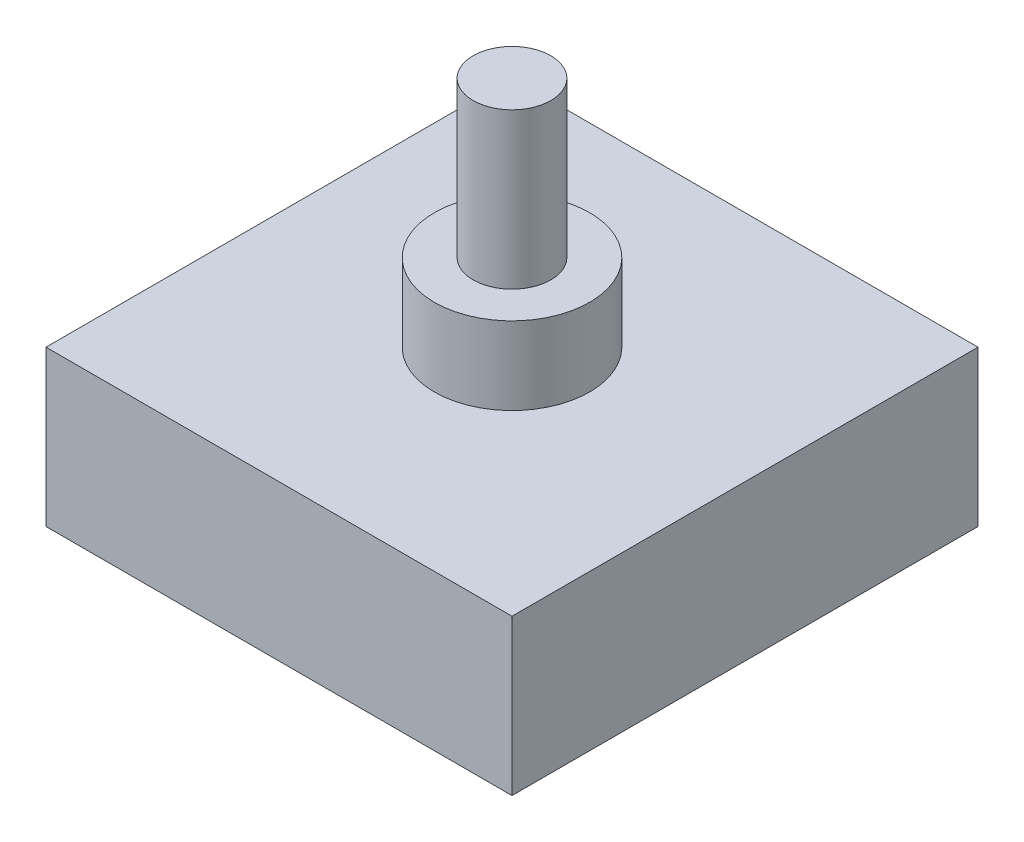
SolidWorks part; units mm, degrees
ref_plane "Front Plane" through (0, 0, 0) normal (0, 0, 1) x (1, 0, 0)
ref_plane "Top Plane" through (0, 0, 0) normal (0, 1, 0) x (1, 0, 0)
ref_plane "Right Plane" through (0, 0, 0) normal (1, 0, 0) x (0, 0, -1)
sketch "Sketch1" plane through (0, 0, 0) normal (0, 1, 0) x (1, 0, 0)
  line L0 (0, 139.7) -> (-74.1744, 139.7) construction
  line L5 (0, 177.8) -> (76.2, 177.8)
  line L6 (0, 177.8) -> (0, 101.6)
  line L7 (0, 101.6) -> (76.2, 101.6)
  line L8 (76.2, 177.8) -> (76.2, 101.6)
  line L9 (0, 279.4) -> (0, 0) construction
  dimension "D1" = 76.2
  dimension "D2" = 76.2
  dimension "D3" = 139.7
extrude "Boss-Extrude1" add sketch "Sketch1" along normal blind 25.4 contours L5 L8 L7 L6
sketch "Sketch2" plane through (0, 25.4, 0) normal (0, 1, 0) x (1, 0, 0)
  line L0 (38.1, 177.8) -> (38.1, 101.6) construction
  line L1 (0, 177.8) -> (76.2, 177.8) construction
  line L2 (0, 101.6) -> (76.2, 101.6) construction
  circle A0 centre (38.1, 139.7) radius 12.7
  dimension "D1" = 25.4
extrude "Boss-Extrude2" add sketch "Sketch2" along normal blind 12.7
sketch "Sketch3" plane through (0, 38.1, 0) normal (0, 1, 0) x (1, 0, 0)
  circle A0 centre (38.1, 139.7) radius 6.35
  circle A1 centre (38.1, 139.7) radius 12.7
  circle A2 centre (38.1, 139.7) radius 12.7 construction
  dimension "D2" = 12.7
  dimension "D1" = 0
extrude "Boss-Extrude3" add sketch "Sketch3" along normal blind 25.4
